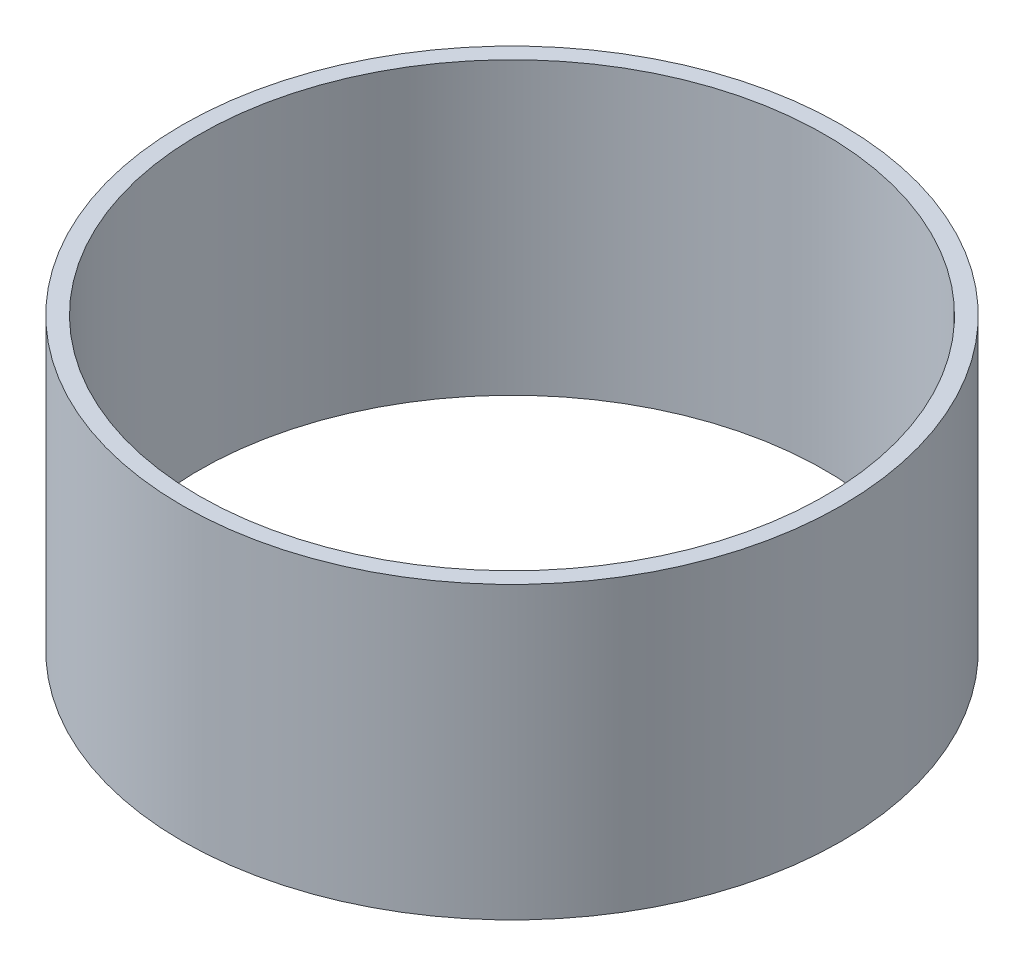
SolidWorks part; units mm, degrees
material "PVC Rigid"
ref_plane "Front Plane" through (0, 0, 0) normal (0, 0, 1) x (1, 0, 0)
ref_plane "Top Plane" through (0, 0, 0) normal (0, 1, 0) x (1, 0, 0)
ref_plane "Right Plane" through (0, 0, 0) normal (1, 0, 0) x (0, 0, -1)
sketch "Sketch1" plane through (0, 0, 0) normal (0, 1, 0) x (1, 0, 0)
  circle A0 centre (0, 0) radius 93.6625
  circle A1 centre (0, 0) radius 88.9
  dimension "D1" = 187.325
  dimension "D2" = 177.8
extrude "Boss-Extrude1" add sketch "Sketch1" along normal mid plane 82.55
ref_plane "Plane1" through (0, 0, 93.6625) normal (0, 0, 1) x (1, 0, 0)
sketch "Sketch2" plane through (0, 0, 93.6625) normal (0, 0, 1) x (1, 0, 0)
  line L0 (0, -45.4025) -> (0, 45.4025) construction
  line L1 (-93.6625, -41.275) -> (93.6625, -41.275) construction
  circle A0 centre (0, -34.925) radius 1.4351
  dimension "D1" = 2.8702
  dimension "D2" = 6.35
extrude "Cut-Extrude1" [suppressed] cut sketch "Sketch2" against normal blind 25.146
pattern_circular "CirPattern1" [suppressed] count 12 over 360
sketch "Sketch3" plane through (0, 0, 93.6625) normal (0, 0, 1) x (1, 0, 0)
  line L0 (0, -45.4025) -> (0, 45.4025) construction
  line L1 (88.9, 41.275) -> (-88.9, 41.275) construction
  circle A1 centre (0, 34.925) radius 1.4351
  dimension "D1" = 2.8702
  dimension "D3" = 6.35
extrude "Cut-Extrude2" [suppressed] cut sketch "Sketch3" against normal blind 25.908
pattern_circular "CirPattern2" [suppressed] count 3 over 360
